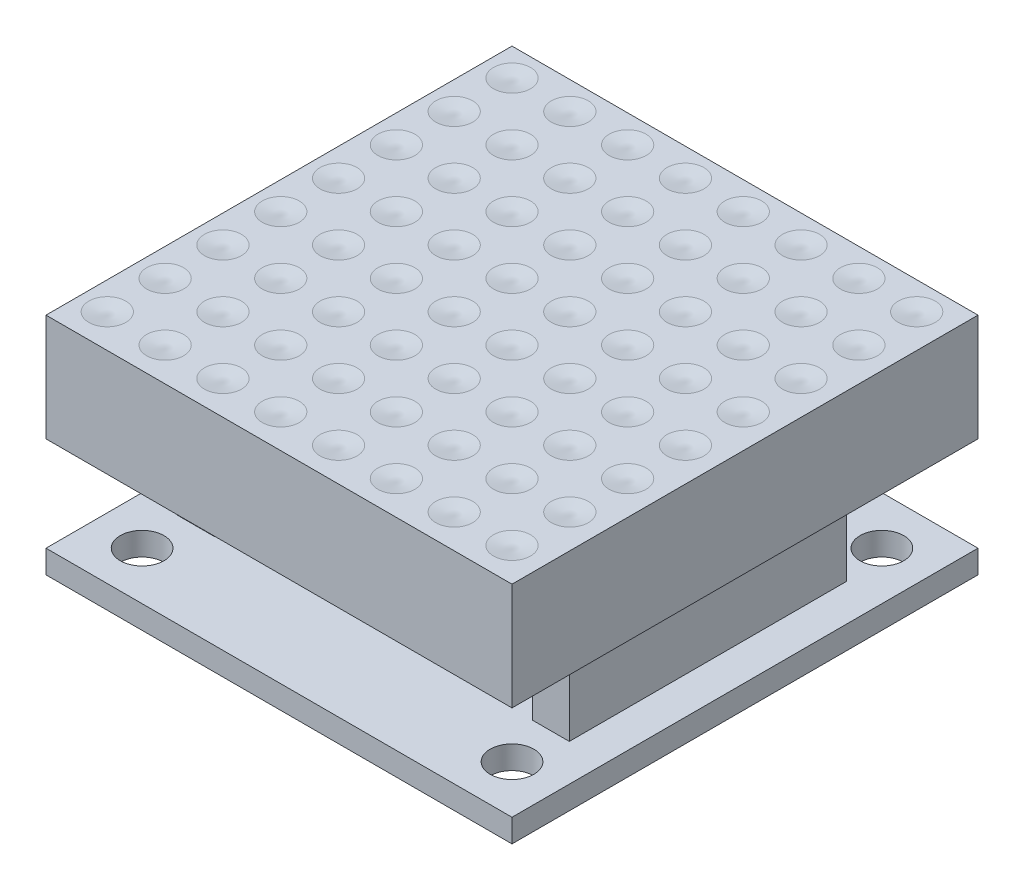
SolidWorks part; units mm, degrees
ref_plane "Front Plane" through (0, 0, 0) normal (0, 0, 1) x (1, 0, 0)
ref_plane "Top Plane" through (0, 0, 0) normal (0, 1, 0) x (1, 0, 0)
ref_plane "Right Plane" through (0, 0, 0) normal (1, 0, 0) x (0, 0, -1)
sketch "Sketch1" plane through (0, 0, 0) normal (0, 1, 0) x (1, 0, 0)
  line L1 (0, 0) -> (32, 0)
  line L2 (0, 0) -> (0, 32)
  line L3 (0, 32) -> (32, 32)
  line L4 (32, 0) -> (32, 32)
  dimension "D1" = 32
  dimension "D2" = 32
extrude "Boss-Extrude1" add sketch "Sketch1" along normal blind 7.36
sketch "Sketch2" plane through (0, 0, 0) normal (0, -1, 0) x (1, 0, 0)
  line L0 (0, -32) -> (0, 0) construction
  line L1 (29.46, -25.525) -> (26.92, -25.525)
  line L2 (29.46, -25.525) -> (29.46, -6.475)
  line L3 (29.46, -6.475) -> (26.92, -6.475)
  line L4 (26.92, -25.525) -> (26.92, -6.475)
  line L5 (5.08, -25.525) -> (2.54, -25.525)
  line L6 (5.08, -25.525) -> (5.08, -6.475)
  line L7 (5.08, -6.475) -> (2.54, -6.475)
  line L8 (2.54, -25.525) -> (2.54, -6.475)
  line L9 (32, 0) -> (32, -32) construction
  line L10 (32, -16) -> (0, -16) construction
  point P14 (5.08, -16)
  point P15 (26.92, -16)
  dimension "D1" = 2.54
  dimension "D2" = 2.54
  dimension "D3" = 2.54
  dimension "D4" = 2.54
  dimension "D5" = 19.05
  dimension "D6" = 19.05
extrude "Boss-Extrude2" add sketch "Sketch2" along normal blind 6.5
sketch "Sketch3" plane through (0, -6.5, 0) normal (0, -1, 0) x (1, 0, 0)
  line L1 (32, -32) -> (0, -32)
  line L2 (32, -32) -> (32, 0)
  line L3 (32, 0) -> (0, 0)
  line L4 (0, 0) -> (0, -32)
  line L5 (0, -32) -> (32, -32)
  line L6 (32, -32) -> (32, 0)
  line L7 (32, 0) -> (0, 0)
  line L8 (0, 0) -> (0, -32) construction
  line L9 (0, -32) -> (32, -32) construction
  line L10 (32, -32) -> (32, 0) construction
  line L11 (32, 0) -> (0, 0) construction
  line L12 (0, -32) -> (0, 0)
  dimension "D1" = 0
extrude "Boss-Extrude3" add sketch "Sketch3" along normal blind 1.5875
sketch "Sketch4" plane through (0, -8.0875, 0) normal (0, -1, 0) x (1, 0, 0)
  line L0 (28.7, -3.3) -> (28.7, -28.7) construction
  line L1 (32, -16) -> (0, -16) construction
  line L2 (32, -32) -> (32, 0) construction
  line L3 (0, 0) -> (0, -32) construction
  line L4 (28.7, -22.8781) -> (3.3, -22.8781) construction
  line L5 (3.3, -3.3) -> (3.3, -28.7) construction
  circle A0 centre (3.3, -28.7) radius 1.5
  circle A1 centre (28.7, -28.7) radius 1.5
  circle A2 centre (28.7, -3.3) radius 1.5
  circle A3 centre (3.3, -3.3) radius 1.5
  point P8 (28.7, -16)
  point P17 (16, -22.8781)
  point P18 (16, -16)
  dimension "D1" = 3
  dimension "D2" = 25.4
  dimension "D3" = 25.4
  dimension "D4" = 25.4
  dimension "D5" = 25.4
extrude "Cut-Extrude1" cut sketch "Sketch4" against normal up to surface (1.5875 mm away) up to face at (3.81, -6.5, -16)
sketch "Sketch5" plane through (0, 7.36, 0) normal (0, 1, 0) x (1, 0, 0)
  line L0 (32, 32) -> (0, 32) construction
  line L1 (0, 32) -> (0, 0) construction
  circle A0 centre (1.905, 30.095) radius 1.27
  dimension "D1" = 2.54
  dimension "D2" = 1.905
  dimension "D3" = 1.905
extrude "Cut-Extrude2" cut sketch "Sketch5" against normal blind 0.254 draft 80
pattern_linear "LPattern1" count 8 spacing 3.97 along (1, 0, 0) count 8 spacing 3.97 along (0, 0, 1) of "Cut-Extrude2"
